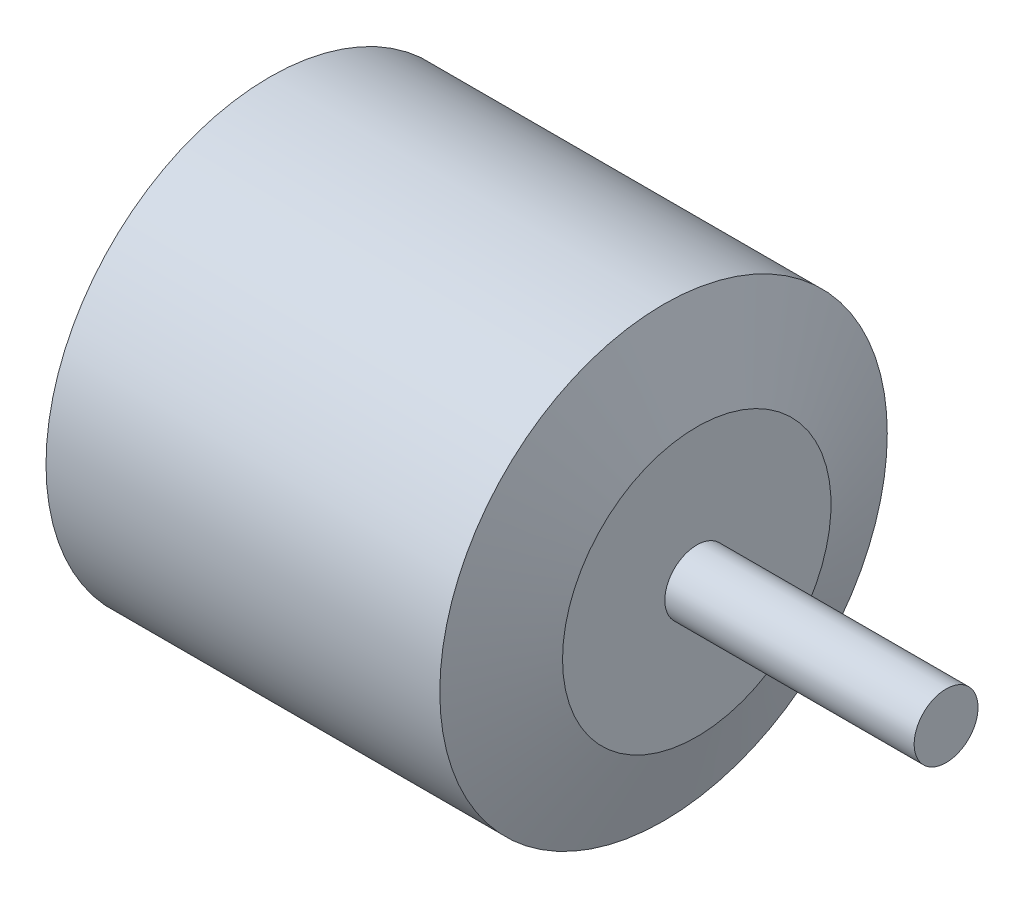
SolidWorks part; units mm, degrees
ref_plane "Front Plane" through (0, 0, 0) normal (0, 0, 1) x (1, 0, 0)
ref_plane "Top Plane" through (0, 0, 0) normal (0, 1, 0) x (1, 0, 0)
ref_plane "Right Plane" through (0, 0, 0) normal (1, 0, 0) x (0, 0, -1)
sketch "Sketch1" plane through (0, 0, 0) normal (0, 0, 1) x (1, 0, 0)
  line L0 (0, 0) -> (0, 2.5)
  line L1 (0, 2.5) -> (-19.5, 2.5)
  line L2 (-19.5, 2.5) -> (-19.5, 10.5)
  line L3 (-19.5, 10.5) -> (-22.1, 17.5)
  line L4 (-22.1, 17.5) -> (-52.9, 17.5)
  line L5 (-52.9, 17.5) -> (-55.5, 10.5)
  line L6 (-55.5, 10.5) -> (-55.5, 5.5)
  line L7 (-55.5, 5.5) -> (-58, 5.5)
  line L8 (-58, 5.5) -> (-58, 0)
  line L9 (-58, 0) -> (0, 0)
  dimension "D1" = 58
  dimension "D2" = 2.5
  dimension "D3" = 38.5
  dimension "D4" = 17.5
  dimension "D5" = 7
  dimension "D6" = 2.6
  dimension "D7" = 5.5
  dimension "D8" = 2.5
revolve "Revolve1" add sketch "Sketch1" angle 360 about L9
